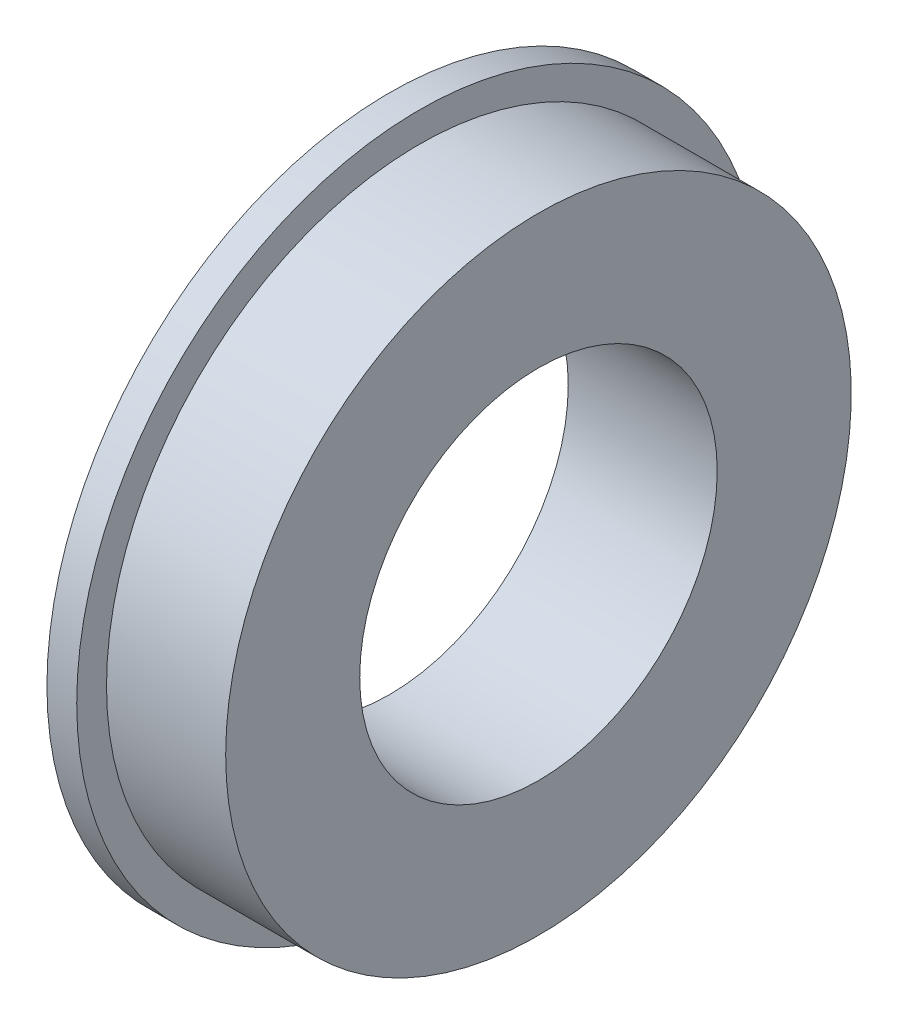
SolidWorks part; units mm, degrees
ref_plane "前视基准面" through (0, 0, 0) normal (0, 0, 1) x (1, 0, 0)
ref_plane "上视基准面" through (0, 0, 0) normal (0, 1, 0) x (1, 0, 0)
ref_plane "右视基准面" through (0, 0, 0) normal (1, 0, 0) x (0, 0, -1)
sketch "草图1" plane through (0, 0, 0) normal (0, 0, 1) x (1, 0, 0)
  line L0 (-18.4954, 0) -> (12.2202, 0) construction
  line L1 (0, 6) -> (-5, 6)
  line L2 (-5, 6) -> (-5, 11.5)
  line L3 (-5, 11.5) -> (-4, 11.5)
  line L4 (-4, 11.5) -> (-4, 10.5)
  line L5 (-4, 10.5) -> (0, 10.5)
  line L6 (0, 10.5) -> (0, 6)
  dimension "D1" = 12
  dimension "D2" = 21
  dimension "D3" = 5
  dimension "D4" = 1
  dimension "D5" = 23
revolve "旋转1" add sketch "草图1" angle 360 about L0
